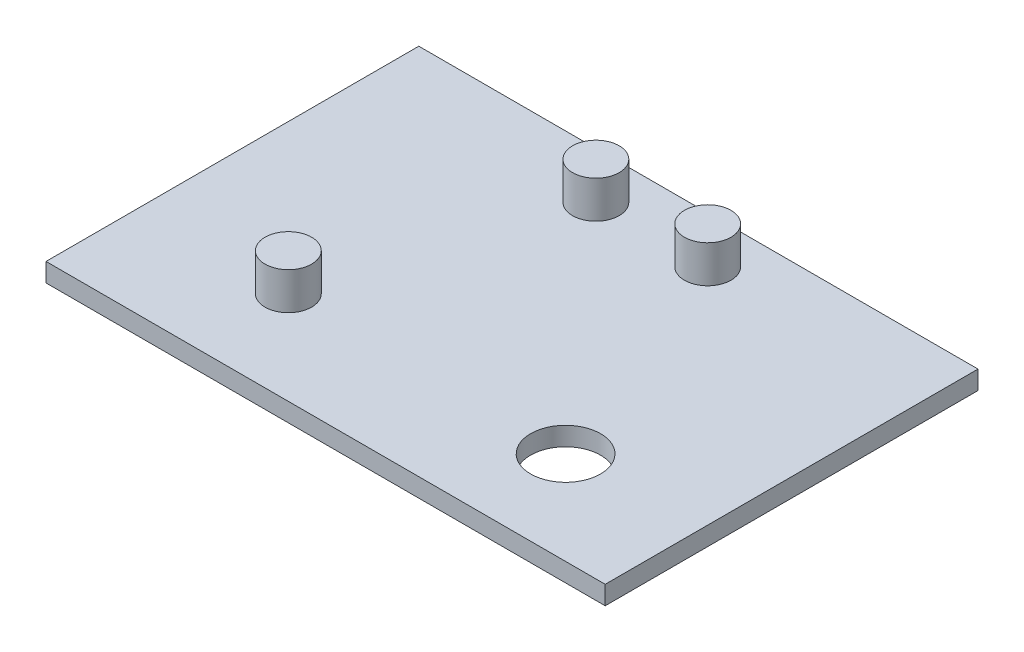
SolidWorks part; units mm, degrees
ref_plane "Front Plane" through (0, 0, 0) normal (0, 0, 1) x (1, 0, 0)
ref_plane "Top Plane" through (0, 0, 0) normal (0, 1, 0) x (1, 0, 0)
ref_plane "Right Plane" through (0, 0, 0) normal (1, 0, 0) x (0, 0, -1)
sketch "Sketch1" plane through (0, 0, 0) normal (0, 1, 0) x (1, 0, 0)
  line L1 (-30, 10) -> (30, 10)
  line L2 (-30, 10) -> (-30, -10)
  line L3 (-30, -10) -> (30, -10)
  line L4 (30, 10) -> (30, -10)
  point P4 (0, 10)
  point P6 (30, 0)
  dimension "D1" = 60
  dimension "D2" = 20
extrude "Boss-Extrude1" add sketch "Sketch1" along normal blind 2
sketch "Sketch2" plane through (0, 2, 0) normal (0, 1, 0) x (1, 0, 0)
  line L0 (-30, 0) -> (-14, 0) construction
  line L1 (-30, 10) -> (-30, -10) construction
  circle A0 centre (-14, 0) radius 2.5
  dimension "D2" = 5
  dimension "D1" = 16
extrude "Boss-Extrude2" add sketch "Sketch2" along normal blind 4
sketch "Sketch3" plane through (0, 2, 0) normal (0, 1, 0) x (1, 0, 0)
  line L0 (-14, 0) -> (15.75, 0) construction
  circle A0 centre (15.75, 0) radius 1
  dimension "D2" = 2
  dimension "D1" = 29.75
extrude "Boss-Extrude3" add sketch "Sketch3" along normal blind 4
sketch "Sketch4" plane through (0, 2, 0) normal (0, 1, 0) x (1, 0, 0)
  circle A0 centre (15.75, 0) radius 3.75
  dimension "D1" = 7.5
extrude "Cut-Extrude1" cut sketch "Sketch4" against normal blind 10 and the other way blind 10
sketch "Sketch5" plane through (0, 2, 0) normal (0, 1, 0) x (1, 0, 0)
  line L1 (-30, 10) -> (30, 10)
  line L2 (-30, 10) -> (-30, 30)
  line L3 (-30, 30) -> (30, 30)
  line L4 (30, 10) -> (30, 30)
  dimension "D1" = 20
extrude "Boss-Extrude4" add sketch "Sketch5" against normal blind 2
sketch "Sketch6" plane through (0, 2, 0) normal (0, 1, 0) x (1, 0, 0)
  line L0 (-30, 25) -> (30, 25) construction
  line L1 (-30, 30) -> (-30, -10) construction
  line L2 (30, -10) -> (30, 30) construction
  line L3 (30, 30) -> (-30, 30) construction
  line L4 (0, 30) -> (0, 25) construction
  circle A0 centre (-6, 25) radius 2.5
  circle A1 centre (6, 25) radius 2.5
  dimension "D2" = 5
  dimension "D3" = 5
  dimension "D4" = 12
  dimension "D1" = 5
  dimension "D5" = 6
extrude "Boss-Extrude5" add sketch "Sketch6" along normal blind 4
